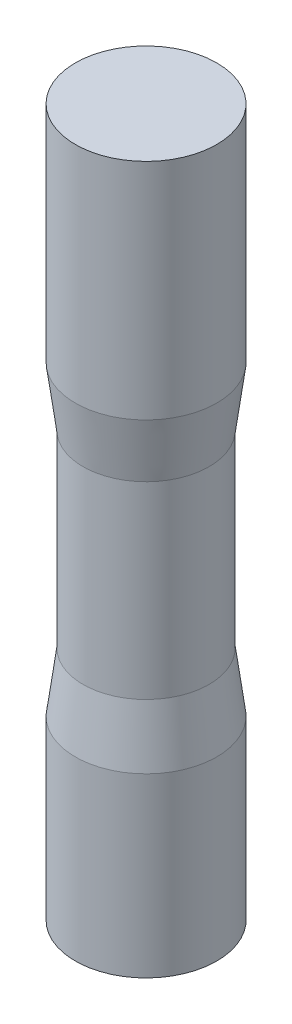
SolidWorks part; units mm, degrees
ref_plane "前视基准面" through (0, 0, 0) normal (0, 0, 1) x (1, 0, 0)
ref_plane "上视基准面" through (0, 0, 0) normal (0, 1, 0) x (1, 0, 0)
ref_plane "右视基准面" through (0, 0, 0) normal (1, 0, 0) x (0, 0, -1)
sketch "草图1" plane through (0, 0, 0) normal (0, 0, 1) x (1, 0, 0)
  line L0 (0, 0) -> (-3, 0)
  line L1 (-3, 0) -> (-3, -9.5)
  line L2 (-3, -9.5) -> (-2.675, -12)
  line L3 (-2.675, -12) -> (-2.675, -20)
  line L4 (-2.675, -20) -> (-3, -22.5)
  line L5 (-3, -22.5) -> (-3, -30)
  line L6 (-3, -30) -> (0, -30)
  line L7 (0, -30) -> (0, 0)
  point P4 (0, 0)
  dimension "D1" = 12
  dimension "D2" = 2.5
  dimension "D3" = 18
  dimension "D4" = 10
  dimension "D5" = 2.5
  dimension "D6" = 3
  dimension "D7" = 2.675
revolve "旋转1" add sketch "草图1" angle 360 about L7
cosmetic thread "装饰螺纹线1" parameters "D2"=4.917
